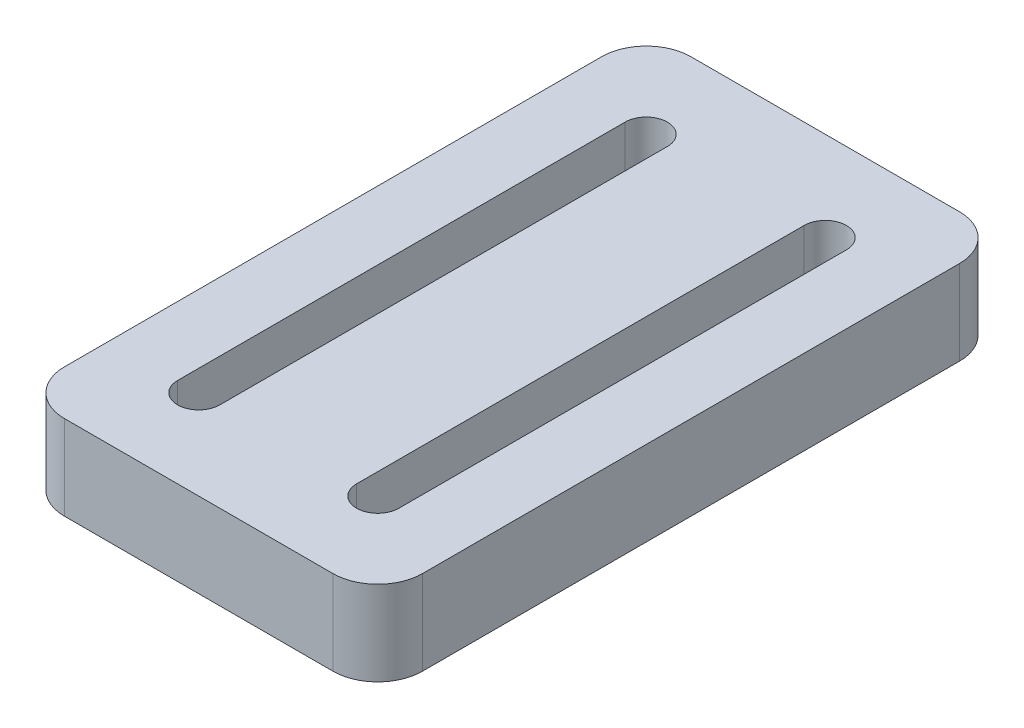
SolidWorks part; units mm, degrees
ref_plane "Front Plane" through (0, 0, 0) normal (0, 0, 1) x (1, 0, 0)
ref_plane "Top Plane" through (0, 0, 0) normal (0, 1, 0) x (1, 0, 0)
ref_plane "Right Plane" through (0, 0, 0) normal (1, 0, 0) x (0, 0, -1)
sketch "Sketch1" plane through (0, 0, 0) normal (0, 1, 0) x (1, 0, 0)
  line L0 (-6.35, -15.875) -> (-6.35, 15.875) construction
  line L1 (12.7, -22.225) -> (-12.7, -22.225)
  line L2 (12.7, -22.225) -> (12.7, 22.225)
  line L3 (12.7, 22.225) -> (-12.7, 22.225)
  line L4 (-12.7, -22.225) -> (-12.7, 22.225)
  line L5 (12.7, -22.225) -> (-12.7, 22.225) construction
  line L6 (12.7, 22.225) -> (-12.7, -22.225) construction
  line L11 (-7.85, -15.875) -> (-7.85, 15.875)
  line L13 (-4.85, -15.875) -> (-4.85, 15.875)
  line L14 (6.35, -15.875) -> (6.35, 15.875) construction
  line L15 (4.85, -15.875) -> (4.85, 15.875)
  line L16 (7.85, -15.875) -> (7.85, 15.875)
  line L17 (-6.35, 15.875) -> (6.35, 15.875) construction
  line L18 (0, 15.875) -> (0, 0) construction
  arc A0 (-7.85, -15.875) -> (-4.85, -15.875) centre (-6.35, -15.875) ccw
  arc A1 (-4.85, 15.875) -> (-7.85, 15.875) centre (-6.35, 15.875) ccw
  arc A2 (4.85, -15.875) -> (7.85, -15.875) centre (6.35, -15.875) ccw
  arc A3 (7.85, 15.875) -> (4.85, 15.875) centre (6.35, 15.875) ccw
  point P0 (0, 0)
  point P6 (0.396, -0.6929)
  point P9 (-6.35, 0)
  point P14 (6.35, 0)
  dimension "D1" = 3
  dimension "D2" = 12.7
  dimension "D3" = 31.75
  dimension "D4" = 6.35
  dimension "D5" = 6.35
extrude "Boss-Extrude1" add sketch "Sketch1" along normal mid plane 6
fillet "Fillet1" radius 3.175 4 edges at (-12.7, 0, -22.225) (12.7, 0, -22.225) (12.7, 0, 22.225) (-12.7, 0, 22.225)
